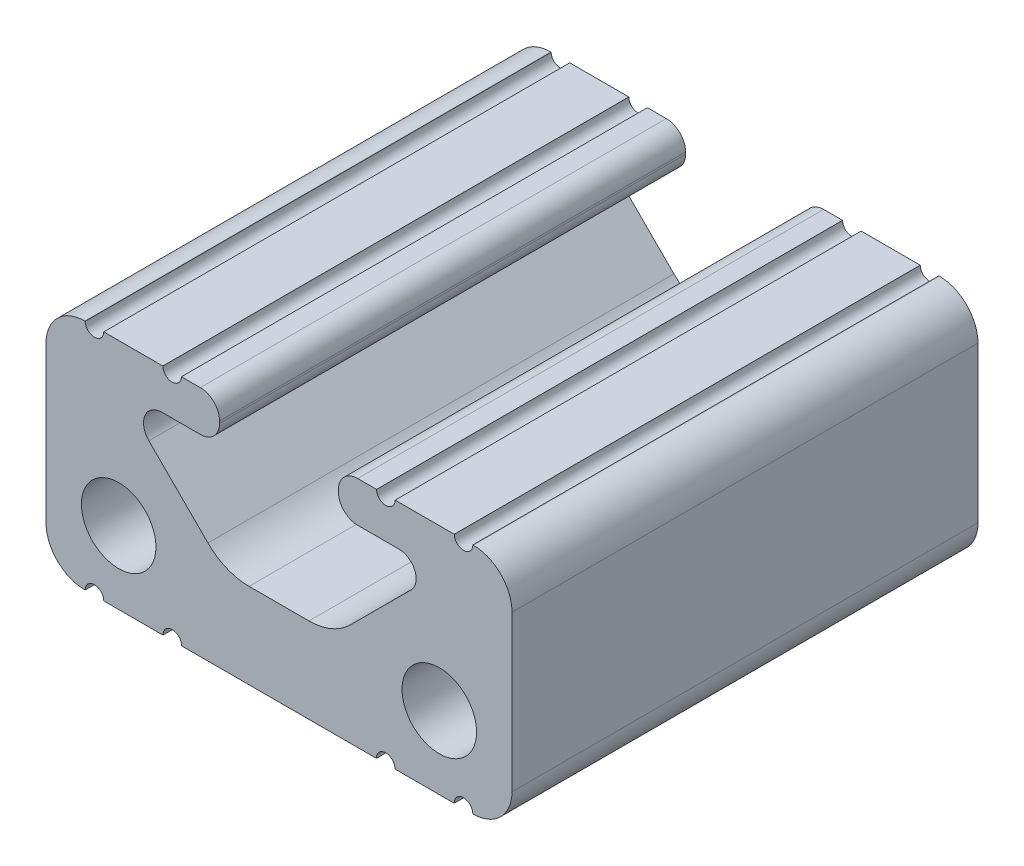
SolidWorks part; units mm, degrees
material "6061 Alloy"
ref_plane "Front Plane" through (0, 0, 0) normal (0, 0, 1) x (1, 0, 0)
ref_plane "Top Plane" through (0, 0, 0) normal (0, 1, 0) x (1, 0, 0)
ref_plane "Right Plane" through (0, 0, 0) normal (1, 0, 0) x (0, 0, -1)
sketch "Sketch1" plane through (0, 0, 0) normal (0, 0, 1) x (1, 0, 0)
  line L21 (9.5511, 6.35) -> (6.331, 6.35)
  line L22 (5.3178, 6.35) -> (4.2875, 6.35)
  line L23 (3.2385, 5.301) -> (3.2385, 5.1892)
  line L24 (4.2875, 4.1402) -> (6.5413, 4.1402)
  line L25 (7.2007, 2.5462) -> (3.8745, -0.7739)
  line L26 (1.6315, -1.7018) -> (-1.6315, -1.7018)
  line L27 (-3.8745, -0.7739) -> (-7.0916, 2.4373)
  line L28 (-6.3872, 4.1402) -> (-4.2875, 4.1402)
  line L29 (-3.2385, 5.1892) -> (-3.2385, 5.301)
  line L30 (-4.2875, 6.35) -> (-5.3192, 6.35)
  line L31 (-6.3324, 6.35) -> (-9.5525, 6.35)
  line L32 (-10.5657, 6.3457) -> (-10.5901, 6.3457)
  line L33 (-12.7, 4.2331) -> (-12.7, -4.2331)
  line L34 (-9.5516, -6.35) -> (-6.323, -6.35)
  line L35 (-5.31, -6.35) -> (5.31, -6.35)
  line L36 (6.323, -6.35) -> (9.5502, -6.35)
  line L37 (10.5633, -6.3403) -> (10.5899, -6.3405)
  line L38 (12.7, -4.2321) -> (12.7, 4.2447)
  line L39 (10.5906, 6.3531) -> (10.5643, 6.3531)
  line L40 (0, -6.35) -> (0, 6.35) construction
  line L41 (-12.7, 0) -> (0, 0) construction
  circle A2 centre (8.7376, -2.3876) radius 2.032
  circle A3 centre (-8.7376, -2.3876) radius 2.032
  arc A26 (9.5511, 6.35) -> (10.5643, 6.3531) centre (10.0577, 6.35) ccw
  arc A27 (5.3178, 6.35) -> (6.331, 6.35) centre (5.8244, 6.35) ccw
  arc A28 (4.2875, 6.35) -> (3.2385, 5.301) centre (4.2875, 5.301) ccw
  arc A29 (3.2385, 5.1892) -> (4.2875, 4.1402) centre (4.2875, 5.1892) ccw
  arc A30 (7.2007, 2.5462) -> (6.5413, 4.1402) centre (6.5413, 3.2068) ccw
  arc A31 (1.6315, -1.7018) -> (3.8745, -0.7739) centre (1.6315, 1.4732) ccw
  arc A32 (-3.8745, -0.7739) -> (-1.6315, -1.7018) centre (-1.6315, 1.4732) ccw
  arc A33 (-6.3872, 4.1402) -> (-7.0916, 2.4373) centre (-6.3872, 3.1431) ccw
  arc A34 (-4.2875, 4.1402) -> (-3.2385, 5.1892) centre (-4.2875, 5.1892) ccw
  arc A35 (-3.2385, 5.301) -> (-4.2875, 6.35) centre (-4.2875, 5.301) ccw
  arc A36 (-6.3324, 6.35) -> (-5.3192, 6.35) centre (-5.8258, 6.35) ccw
  arc A37 (-10.5657, 6.3457) -> (-9.5525, 6.35) centre (-10.0591, 6.35) ccw
  arc A38 (-10.5901, 6.3457) -> (-12.7, 4.2331) centre (-10.5916, 4.2373) ccw
  arc A39 (-12.7, -4.2331) -> (-10.5647, -6.3413) centre (-10.5916, -4.2331) ccw
  arc A40 (-9.5516, -6.35) -> (-10.5647, -6.3413) centre (-10.0581, -6.3412) ccw
  arc A41 (-5.31, -6.35) -> (-6.323, -6.35) centre (-5.8165, -6.3412) ccw
  arc A42 (6.323, -6.35) -> (5.31, -6.35) centre (5.8165, -6.3412) ccw
  arc A43 (10.5633, -6.3403) -> (9.5502, -6.35) centre (10.0567, -6.3412) ccw
  arc A44 (10.5899, -6.3405) -> (12.7, -4.2321) centre (10.5916, -4.2321) ccw
  arc A45 (12.7, 4.2447) -> (10.5906, 6.3531) centre (10.5916, 4.2447) ccw
  dimension "D3" = 4.064
  dimension "D7" = 14.859
  dimension "D10" = 8.7376
  dimension "D4" = 3.9624
  dimension "D1" = 17.4752
  dimension "D2" = 25.4
  dimension "D5" = 12.7
  dimension "D6" = 2.2098
  dimension "D8" = 6.477
  dimension "D9" = 5.842
extrude "Extrude1" add sketch "Sketch1" against normal blind 25.4
